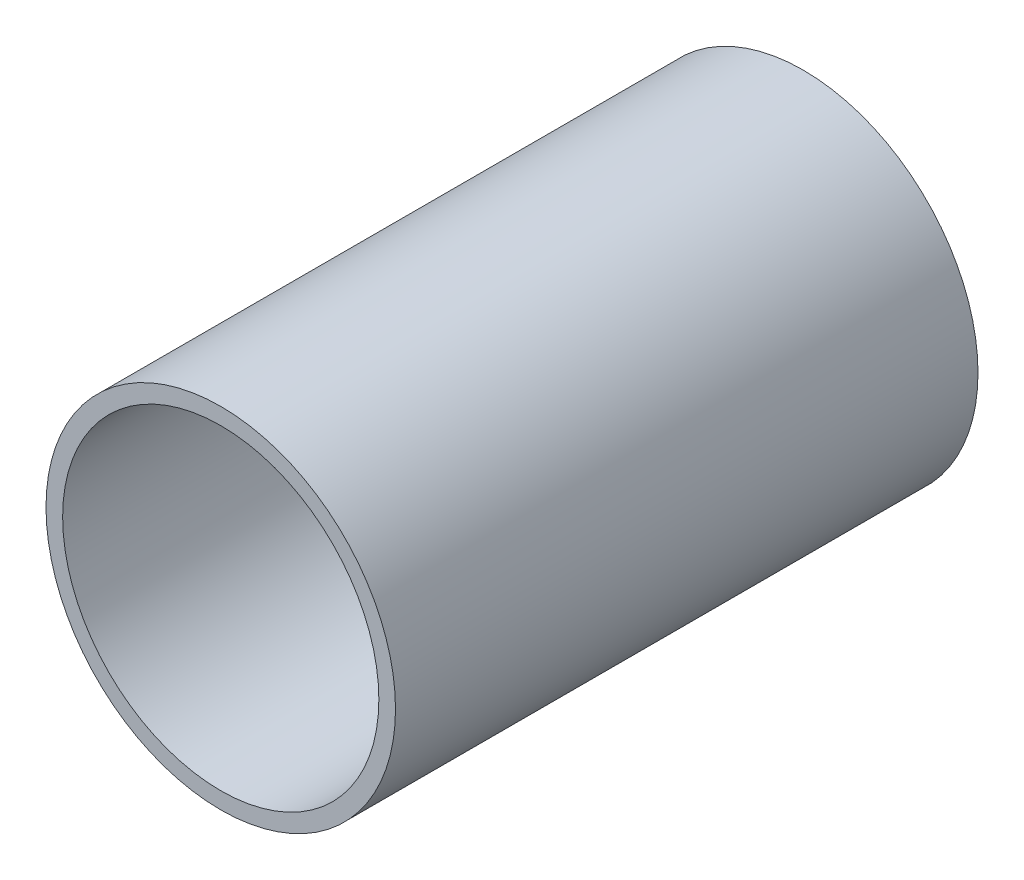
SolidWorks part; units mm, degrees
ref_plane "Front Plane" through (0, 0, 0) normal (0, 0, 1) x (1, 0, 0)
ref_plane "Top Plane" through (0, 0, 0) normal (0, 1, 0) x (1, 0, 0)
ref_plane "Right Plane" through (0, 0, 0) normal (1, 0, 0) x (0, 0, -1)
sketch "Sketch1" plane through (0, 0, 0) normal (0, 0, 1) x (1, 0, 0)
  circle A0 centre (0, 0) radius 19
  circle A1 centre (0, 0) radius 21
  dimension "D1" = 38
  dimension "D2" = 2
extrude "Boss-Extrude1" add sketch "Sketch1" along normal blind 70
